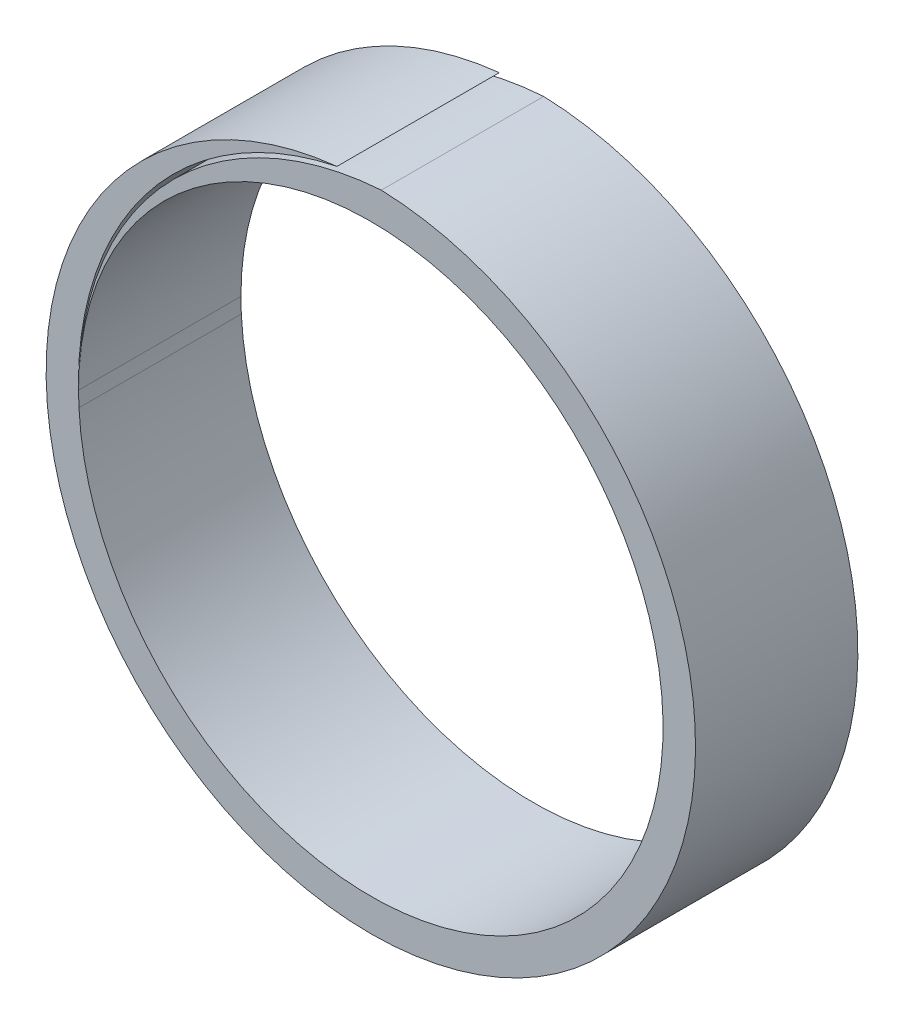
SolidWorks part; units mm, degrees
ref_plane "Front Plane" through (0, 0, 0) normal (0, 0, 1) x (1, 0, 0)
ref_plane "Top Plane" through (0, 0, 0) normal (0, 1, 0) x (1, 0, 0)
ref_plane "Right Plane" through (0, 0, 0) normal (1, 0, 0) x (0, 0, -1)
sketch "Sketch1" plane through (0, 0, 0) normal (0, 0, 1) x (1, 0, 0)
  circle A0 centre (0, 0) radius 17.75 construction
  arc A1 (-2.0857, 19.891) -> (0.6471, 19.9895) centre (0, 0) ccw
  arc A2 (-17.976, -0.9294) -> (-18, 0) centre (0, 0) ccw
  arc A3 (-18, 0) -> (0.6471, 19.9895) centre (2, 0.0353) cw
  arc A4 (-17.976, -0.9294) -> (-2.0857, 19.891) centre (1.9856, 0.3097) cw
  dimension "D1" = 35.5
  dimension "D2" = 36
  dimension "D3" = 40
  dimension "D4" = 20
  dimension "D5" = 20
extrude "Boss-Extrude1" add sketch "Sketch1" along normal blind 10
